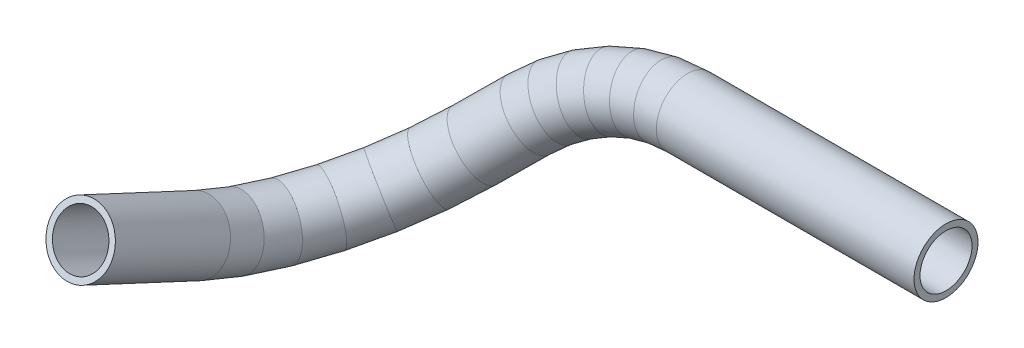
SolidWorks part; units mm, degrees
ref_plane "Front Plane" through (0, 0, 0) normal (0, 0, 1) x (1, 0, 0)
ref_plane "Top Plane" through (0, 0, 0) normal (0, 1, 0) x (1, 0, 0)
ref_plane "Right Plane" through (0, 0, 0) normal (1, 0, 0) x (0, 0, -1)
sketch3d "Path"
  line L0 (34.8, 56.8867, -67.7949) -> (-3.6588, 56.8867, -67.7949)
  line L1 (-3.6588, 56.8867, -67.7949) -> (-7.1777, 56.6773, -67.6419)
  line L2 (-7.1777, 56.6773, -67.6419) -> (-10.6205, 56.0536, -67.1861)
  line L3 (-10.6205, 56.0536, -67.1861) -> (-13.9128, 55.0291, -66.4375)
  line L4 (-13.9128, 55.0291, -66.4375) -> (-16.9835, 53.6259, -65.4121)
  line L5 (-16.9835, 53.6259, -65.4121) -> (-19.7662, 51.8743, -64.1322)
  line L6 (-19.7662, 51.8743, -64.1322) -> (-22.2007, 49.8123, -62.6254)
  line L7 (-22.2007, 49.8123, -62.6254) -> (-26.8926, 45.2027, -59.257)
  line L8 (-26.8926, 45.2027, -59.257) -> (-30.4029, 42.0402, -56.123)
  line L9 (-30.4029, 42.0402, -56.123) -> (-33.5888, 39.753, -52.0285)
  line L10 (-33.5888, 39.753, -52.0285) -> (-36.2723, 38.4687, -47.2021)
  line L11 (-36.2723, 38.4687, -47.2021) -> (-38.3039, 38.2591, -41.913)
  line L12 (-38.3039, 38.2591, -41.913) -> (-39.57, 39.1357, -36.4564)
  line L13 (-39.57, 39.1357, -36.4564) -> (-40, 41.0498, -31.137)
  line L14 (-40, 41.0498, -31.137) -> (-40, 49.1454, -13.7759)
ref_plane "Start Plane" through (34.8, 0, 0) normal (1, 0, 0) x (0, 0, -1)
sketch "Profile" plane through (34.8, 0, 0) normal (1, 0, 0) x (0, 0, -1)
  circle A0 centre (67.7949, 56.8867) radius 4.7625
  circle A1 centre (67.7949, 56.8867) radius 3.8735
sweep "Tube" add profiles "Profile" path "Path"
